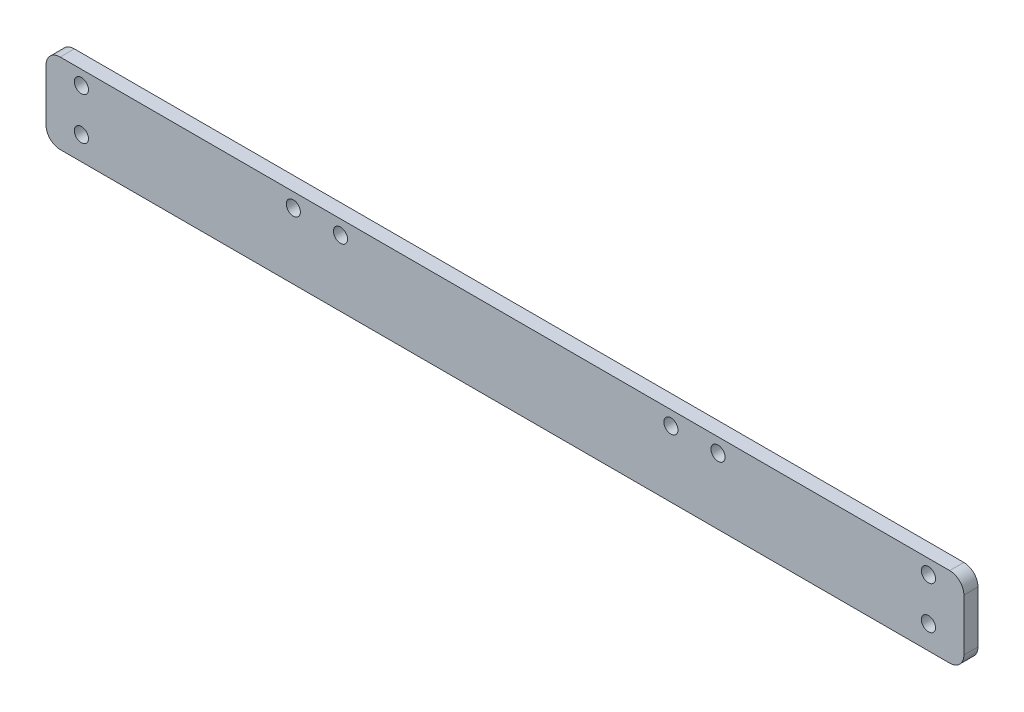
SolidWorks part; units mm, degrees
ref_plane "前视基准面" through (0, 0, 0) normal (0, 0, 1) x (1, 0, 0)
ref_plane "上视基准面" through (0, 0, 0) normal (0, 1, 0) x (1, 0, 0)
ref_plane "右视基准面" through (0, 0, 0) normal (1, 0, 0) x (0, 0, -1)
sketch "草图1" plane through (0, 0, 0) normal (0, 0, 1) x (1, 0, 0)
  line L1 (-97.3, -8.5) -> (97.3, -8.5)
  line L2 (-97.3, -8.5) -> (-97.3, 8.5)
  line L3 (-97.3, 8.5) -> (97.3, 8.5)
  line L4 (97.3, -8.5) -> (97.3, 8.5)
  line L5 (-97.3, -8.5) -> (97.3, 8.5) construction
  line L6 (-97.3, 8.5) -> (97.3, -8.5) construction
  point P0 (0, 0)
  dimension "D1" = 194.6
  dimension "D2" = 17
extrude "凸台-拉伸1" add sketch "草图1" along normal blind 3
fillet "圆角1" radius 3 4 edges at (97.3, -8.5, 1.5) (97.3, 8.5, 1.5) (-97.3, -8.5, 1.5) (-97.3, 8.5, 1.5)
sketch "草图2" plane through (0, 0, 3) normal (0, 0, 1) x (1, 0, 0)
  circle A4 centre (89.8002, 5.5) radius 1.5
  circle A5 centre (89.8002, -3.5) radius 1.5
  circle A6 centre (-89.8, -3.5) radius 1.5
  circle A7 centre (-89.8, 5.5) radius 1.5
extrude "切除-拉伸1" cut sketch "草图2" against normal blind 3
sketch "草图3" plane through (0, 0, 0) normal (0, 0, -1) x (-1, 0, 0)
  circle A2 centre (44.8638, 5.5) radius 1.5
  circle A3 centre (34.8638, 5.5) radius 1.5
extrude "切除-拉伸2" cut sketch "草图3" against normal blind 3
sketch "草图5" plane through (0, 0, 0) normal (0, 0, -1) x (-1, 0, 0)
  circle A2 centre (-45.1883, 5.5) radius 1.5
  circle A3 centre (-35.1883, 5.5) radius 1.5
extrude "切除-拉伸3" cut sketch "草图5" against normal blind 3
